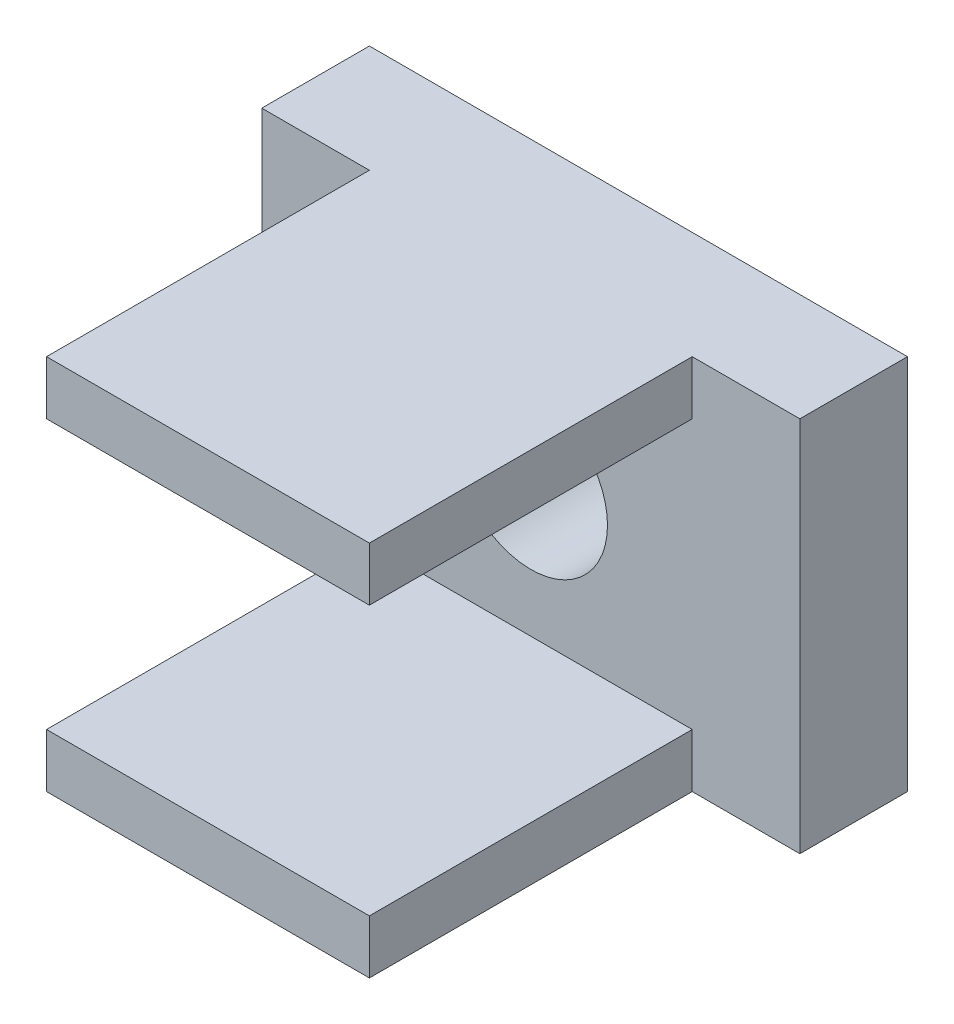
SolidWorks part; units mm, degrees
ref_plane "Front Plane" through (0, 0, 0) normal (0, 0, 1) x (1, 0, 0)
ref_plane "Top Plane" through (0, 0, 0) normal (0, 1, 0) x (1, 0, 0)
ref_plane "Right Plane" through (0, 0, 0) normal (1, 0, 0) x (0, 0, -1)
sketch "Sketch1" plane through (0, 0, 0) normal (0, 0, 1) x (1, 0, 0)
  line L1 (-5, -3.5) -> (5, -3.5)
  line L2 (-5, -3.5) -> (-5, 3.5)
  line L3 (-5, 3.5) -> (5, 3.5)
  line L4 (5, -3.5) -> (5, 3.5)
  line L5 (-5, -3.5) -> (5, 3.5) construction
  line L6 (-5, 3.5) -> (5, -3.5) construction
  point P0 (0, 0)
  dimension "D1" = 10
  dimension "D2" = 7
extrude "Boss-Extrude1" add sketch "Sketch1" along normal mid plane 2
sketch "Sketch2" plane through (0, 0, 1) normal (0, 0, 1) x (1, 0, 0)
  circle A0 centre (0, 0) radius 1.425
  dimension "D1" = 2.85
extrude "Cut-Extrude1" cut sketch "Sketch2" against normal through all
sketch "Sketch3" plane through (0, 0, 1) normal (0, 0, 1) x (1, 0, 0)
  line L0 (5, 3.5) -> (-5, 3.5) construction
  line L1 (-3, 2.5) -> (3, 2.5)
  line L2 (-3, 2.5) -> (-3, 3.5)
  line L3 (-3, 3.5) -> (3, 3.5)
  line L4 (3, 2.5) -> (3, 3.5)
  line L5 (-3, 2.5) -> (3, 3.5) construction
  line L6 (-3, 3.5) -> (3, 2.5) construction
  line L7 (0, 0) -> (0, 3.5) construction
  point P0 (0, 3)
  dimension "D1" = 1
  dimension "D2" = 6
extrude "Boss-Extrude2" add sketch "Sketch3" along normal blind 6
mirror "Mirror1" about plane through (0, 0, 0) normal (0, 1, 0) of "Boss-Extrude2"
